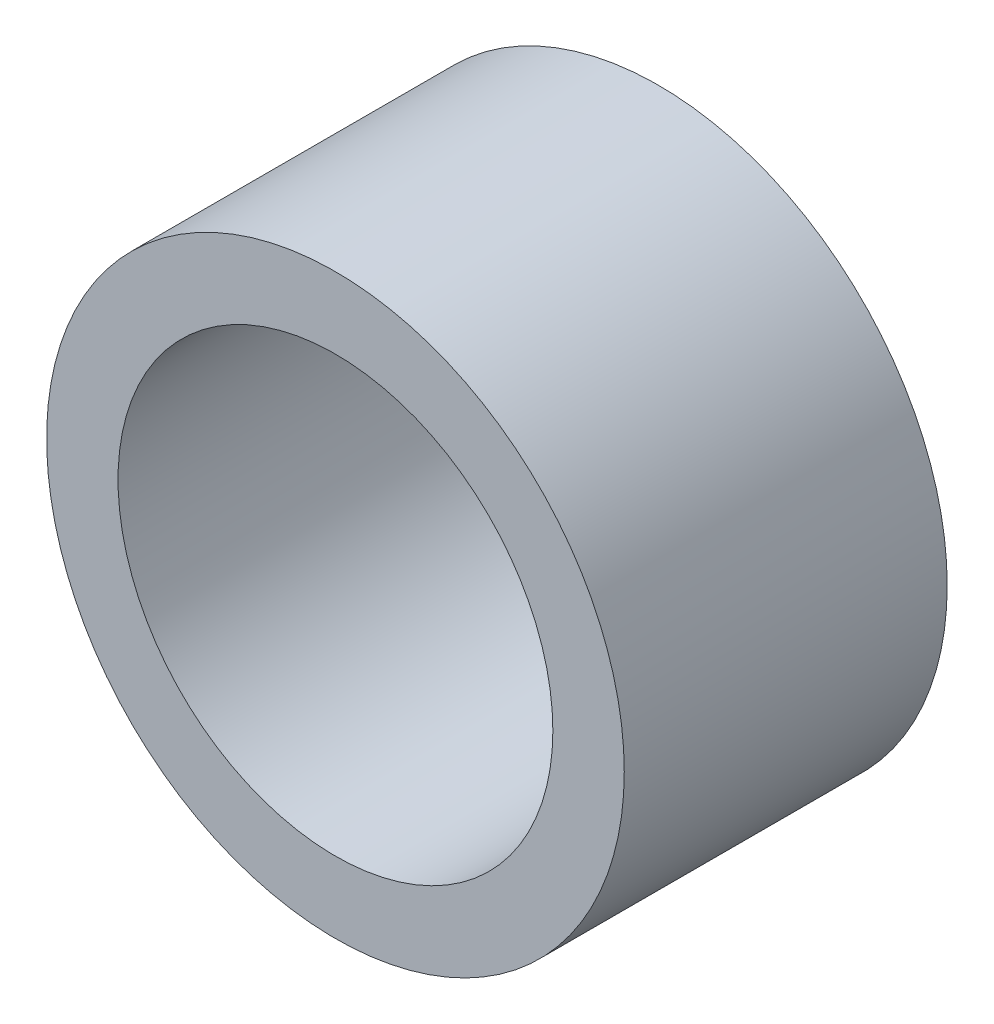
SolidWorks part; units mm, degrees
material "Cast Alloy Steel"
ref_plane "Front Plane" through (0, 0, 0) normal (0, 0, 1) x (1, 0, 0)
ref_plane "Top Plane" through (0, 0, 0) normal (0, 1, 0) x (1, 0, 0)
ref_plane "Right Plane" through (0, 0, 0) normal (1, 0, 0) x (0, 0, -1)
sketch "Sketch1" plane through (0, 0, 0) normal (0, 0, 1) x (1, 0, 0)
  circle A0 centre (0, 0) radius 12.7
  circle A1 centre (0, 0) radius 9.56
extrude "Boss-Extrude1" add sketch "Sketch1" along normal blind 14.2
